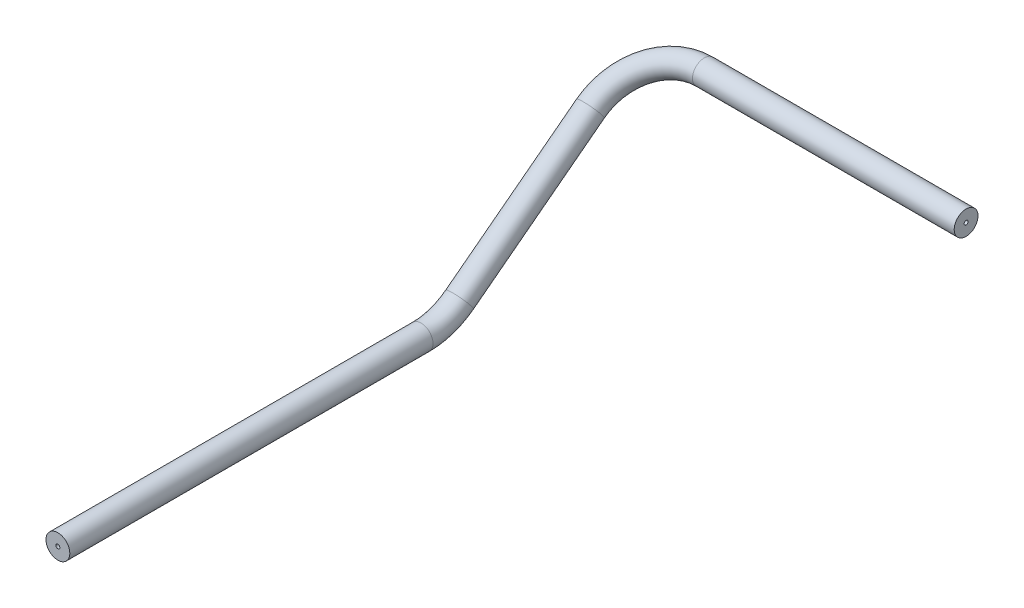
SolidWorks part; units mm, degrees
ref_plane "Front Plane" through (0, 0, 0) normal (0, 0, 1) x (1, 0, 0)
ref_plane "Top Plane" through (0, 0, 0) normal (0, 1, 0) x (1, 0, 0)
ref_plane "Right Plane" through (0, 0, 0) normal (1, 0, 0) x (0, 0, -1)
sketch "Skica1" plane through (0, 0, 0) normal (0, 0, 1) x (1, 0, 0)
  line L0 (0, 0) -> (82, 0)
  dimension "D1" = 82
sketch "Skica3" plane through (0, 0, 0) normal (1, 0, 0) x (0, 0, -1)
  line L0 (0, 0) -> (-50, -38.2)
  line L1 (-50, -38.2) -> (-147, -38.2)
  dimension "D1" = 147
  dimension "D2" = 50
  dimension "D3" = 38.2
ref_plane "Rovina1" through (82, 0, 0) normal (1, 0, 0) x (0, 0, -1)
sketch "Skica4" plane through (82, 0, 0) normal (1, 0, 0) x (0, 0, -1)
  circle A0 centre (0, 0) radius 3
  circle A1 centre (0, 0) radius 0.5
  dimension "D1" = 6
  dimension "D2" = 2.5
sketch3d "3DSkica1"
  line L0 (82, 0, 0) -> (16, 0, 0)
  line L1 (0, -9.7135, 12.7141) -> (0, -34.9141, 45.699)
  line L2 (0, -38.2, 55.4126) -> (0, -38.2, 147)
  arc A0 (0, -34.9141, 45.699) -> (0, -38.2, 55.4126) centre (0, -22.2, 55.4126) ccw
  arc A1 (16, 0, 0) -> (0, -9.7135, 12.7141) centre (16, -9.7135, 12.7141) ccw
  point P10 (0, -38.2, 50)
  point P11 (-16, -22.2, 55.4126)
  point P14 (0, 0, 0)
  point P15 (16, 3.0005, 22.4276)
  dimension "D1" = 16
sweep "Táhnout po křivce1" add profiles "Skica4" path "3DSkica1"
